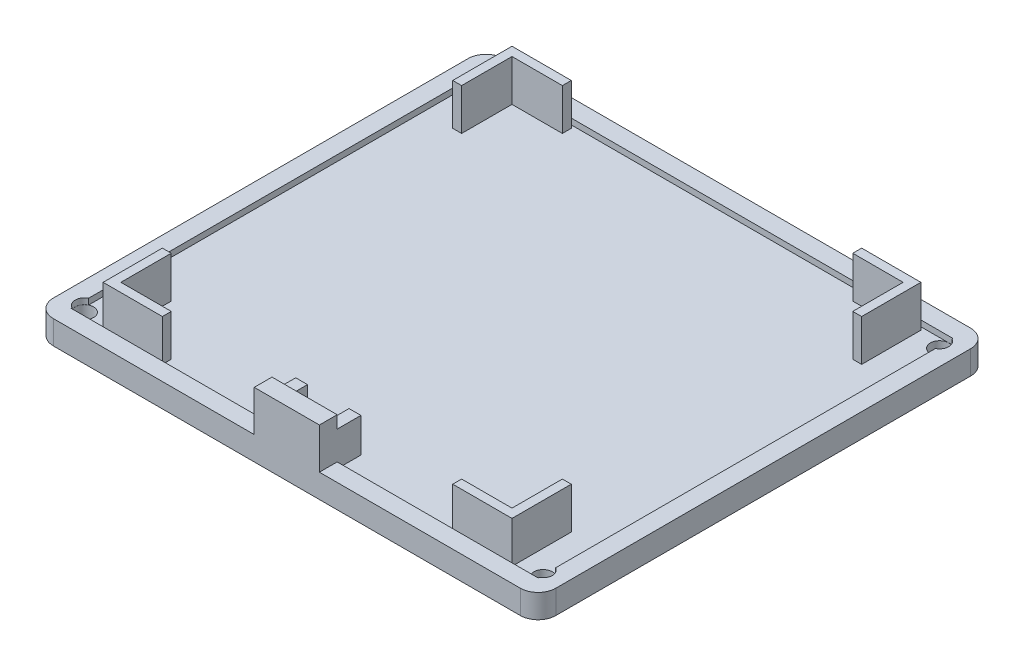
SolidWorks part; units mm, degrees
ref_plane "Front Plane" through (0, 0, 0) normal (0, 0, 1) x (1, 0, 0)
ref_plane "Top Plane" through (0, 0, 0) normal (0, 1, 0) x (1, 0, 0)
ref_plane "Right Plane" through (0, 0, 0) normal (1, 0, 0) x (0, 0, -1)
sketch "Sketch2" plane through (0, 0, 0) normal (0, 1, 0) x (1, 0, 0)
  line L1 (-42.4, 38) -> (42.4, 38)
  line L2 (-42.4, 38) -> (-42.4, -38)
  line L3 (-42.4, -38) -> (42.4, -38)
  line L4 (42.4, 38) -> (42.4, -38)
  line L5 (-42.4, 38) -> (42.4, -38) construction
  line L6 (-42.4, -38) -> (42.4, 38) construction
  line L7 (-38.7, -33.44) -> (38.7, -33.44) construction
  line L8 (-38.7, -33.44) -> (-38.7, 33.44) construction
  line L9 (-38.7, 33.44) -> (38.7, 33.44) construction
  line L10 (38.7, -33.44) -> (38.7, 33.44) construction
  line L11 (-38.7, -33.44) -> (38.7, 33.44) construction
  line L12 (-38.7, 33.44) -> (38.7, -33.44) construction
  circle A0 centre (38.7, 33.44) radius 1.55
  circle A1 centre (38.7, -33.44) radius 1.55
  circle A2 centre (-38.7, 33.44) radius 1.55
  circle A3 centre (-38.7, -33.44) radius 1.55
  point P0 (0, 0)
  point P5 (0, 0)
  dimension "D5" = 3.1
  dimension "D1" = 76
  dimension "D2" = 84.8
  dimension "D3" = 77.4
  dimension "D4" = 66.88
extrude "Boss-Extrude1" add sketch "Sketch2" along normal blind 3
sketch "Sketch3" plane through (0, 3, 0) normal (0, 1, 0) x (1, 0, 0)
  line L0 (-42.4, -38) -> (42.4, -38) construction
  line L1 (-5.5, -38) -> (5.5, -38)
  line L2 (-5.5, -38) -> (-5.5, -35)
  line L3 (-5.5, -35) -> (5.5, -35)
  line L4 (5.5, -38) -> (5.5, -35)
  line L5 (0, 0) -> (0, -35) construction
  dimension "D1" = 11
  dimension "D2" = 3
extrude "Boss-Extrude2" add sketch "Sketch3" along normal blind 7.9
fillet "Fillet1" radius 3 4 edges at (42.4, 1.5, -38) (-42.4, 1.5, -38) (42.4, 1.5, 38) (-42.4, 1.5, 38)
sketch "Sketch4" plane through (0, 3, 0) normal (0, 1, 0) x (1, 0, 0)
  line L0 (5.5, -38) -> (39.4, -38) construction
  line L1 (-5.5, -38) -> (5.5, -38) construction
  line L2 (-39.4, -38) -> (-5.5, -38) construction
  line L3 (42.4, -35) -> (42.4, 35) construction
  line L4 (-42.4, 35) -> (-42.4, -35) construction
  line L5 (39.4, 38) -> (-39.4, 38) construction
  line L6 (5.5, -38) -> (39.4, -38)
  line L25 (-5.5, -38) -> (5.5, -38)
  line L26 (-39.4, -38) -> (-5.5, -38)
  line L27 (42.4, -35) -> (42.4, 35)
  line L28 (-42.4, 35) -> (-42.4, -35)
  line L29 (39.4, 38) -> (-39.4, 38)
  line L30 (39.4, -35) -> (39.4, -34.8341)
  line L31 (39.4, 35) -> (-39.4, 35)
  line L32 (-39.4, 35) -> (-39.4, 34.8341)
  line L33 (-39.4, -35) -> (-5.5, -35)
  line L34 (-5.5, -35) -> (5.5, -35)
  line L35 (5.5, -35) -> (39.4, -35)
  line L36 (-39.4, 32.0459) -> (-39.4, -32.0459)
  line L37 (-39.4, 35) -> (-39.4, -35) construction
  line L38 (39.4, 34.8341) -> (39.4, 35)
  line L39 (39.4, -35) -> (39.4, 35) construction
  line L40 (39.4, -32.0459) -> (39.4, 32.0459)
  line L41 (-39.4, -34.8341) -> (-39.4, -35)
  arc A0 (39.4, -38) -> (42.4, -35) centre (39.4, -35) ccw construction
  arc A1 (-42.4, -35) -> (-39.4, -38) centre (-39.4, -35) ccw construction
  arc A2 (42.4, 35) -> (39.4, 38) centre (39.4, 35) ccw construction
  arc A3 (-39.4, 38) -> (-42.4, 35) centre (-39.4, 35) ccw construction
  arc A16 (39.4, -38) -> (42.4, -35) centre (39.4, -35) ccw
  arc A17 (-42.4, -35) -> (-39.4, -38) centre (-39.4, -35) ccw
  arc A18 (42.4, 35) -> (39.4, 38) centre (39.4, 35) ccw
  arc A19 (-39.4, 38) -> (-42.4, 35) centre (-39.4, 35) ccw
  arc A20 (-39.4, 34.8341) -> (-39.4, 32.0459) centre (-38.7, 33.44) ccw
  arc A21 (39.4, 32.0459) -> (39.4, 34.8341) centre (38.7, 33.44) ccw
  arc A22 (39.4, -34.8341) -> (39.4, -32.0459) centre (38.7, -33.44) ccw
  arc A23 (-39.4, -32.0459) -> (-39.4, -34.8341) centre (-38.7, -33.44) ccw
  arc A24 (39.4, -35) -> (39.4, -35) centre (39.4, -35) ccw
  arc A25 (39.4, 35) -> (39.4, 35) centre (39.4, 35) ccw
  arc A26 (-39.4, 35) -> (-39.4, 35) centre (-39.4, 35) ccw
  arc A27 (-39.4, -35) -> (-39.4, -35) centre (-39.4, -35) ccw
  dimension "D1" = 3
extrude "Boss-Extrude3" add sketch "Sketch4" along normal blind 1
sketch "Sketch9" plane through (0, 3, 0) normal (0, 1, 0) x (1, 0, 0)
  line L1 (-34.5, 34.5) -> (34.5, 34.5) construction
  line L2 (-34.5, 34.5) -> (-34.5, -34.5) construction
  line L3 (-34.5, -34.5) -> (34.5, -34.5) construction
  line L4 (34.5, 34.5) -> (34.5, -34.5) construction
  line L5 (-34.5, 34.5) -> (34.5, -34.5) construction
  line L6 (-34.5, -34.5) -> (34.5, 34.5) construction
  line L7 (-34.5, 34.5) -> (-24.5, 34.5)
  line L8 (-34.5, 34.5) -> (-34.5, 24.5)
  line L9 (-33, 33) -> (-24.5, 33)
  line L10 (-24.5, 34.5) -> (-24.5, 33)
  line L13 (-34.5, 24.5) -> (-33, 24.5)
  line L14 (-33, 33) -> (-33, 24.5)
  line L15 (34.5, 34.5) -> (24.5, 34.5)
  line L17 (33, 33) -> (24.5, 33)
  line L18 (24.5, 34.5) -> (24.5, 33)
  line L20 (34.5, 34.5) -> (34.5, 24.5)
  line L21 (34.5, 24.5) -> (33, 24.5)
  line L22 (33, 33) -> (33, 24.5)
  line L24 (34.5, -34.5) -> (34.5, -24.5)
  line L25 (34.5, -24.5) -> (33, -24.5)
  line L26 (33, -33) -> (33, -24.5)
  line L27 (34.5, -34.5) -> (24.5, -34.5)
  line L29 (33, -33) -> (24.5, -33)
  line L30 (24.5, -34.5) -> (24.5, -33)
  line L32 (-34.5, -34.5) -> (-34.5, -24.5)
  line L33 (-34.5, -24.5) -> (-33, -24.5)
  line L34 (-33, -33) -> (-33, -24.5)
  line L35 (-34.5, -34.5) -> (-24.5, -34.5)
  line L37 (-33, -33) -> (-24.5, -33)
  line L38 (-24.5, -34.5) -> (-24.5, -33)
  point P0 (0, 0)
  dimension "D1" = 69
  dimension "D2" = 1.5
  dimension "D3" = 10
extrude "Boss-Extrude5" add sketch "Sketch9" along normal blind 7
sketch "Sketch10" plane through (0, 0, 0) normal (0, -1, 0) x (1, 0, 0)
  circle A0 centre (-38.7, 33.44) radius 2.55
  circle A1 centre (38.7, 33.44) radius 2.55
  circle A2 centre (38.7, -33.44) radius 2.55
  circle A3 centre (-38.7, -33.44) radius 2.55
  dimension "D1" = 5.1
extrude "Cut-Extrude2" cut sketch "Sketch10" against normal blind 1
sketch "Sketch11" plane through (0, 0, 0) normal (0, -1, 0) x (1, 0, 0)
  text T0 "90W" font "Century Gothic" height in points 48
extrude "Cut-Extrude3" cut sketch "Sketch11" against normal blind 1
sketch "Sketch13" plane through (0, 3, 0) normal (0, 1, 0) x (1, 0, 0)
  line L1 (-5.5, -35) -> (-3.5, -35)
  line L2 (-5.5, -35) -> (-5.5, -31)
  line L3 (-5.5, -31) -> (-3.5, -31)
  line L4 (-3.5, -35) -> (-3.5, -31)
  line L5 (5.5, -35) -> (3.5, -35)
  line L6 (5.5, -35) -> (5.5, -31)
  line L7 (5.5, -31) -> (3.5, -31)
  line L8 (3.5, -35) -> (3.5, -31)
  dimension "D1" = 4
  dimension "D2" = 4
  dimension "D3" = 2
  dimension "D4" = 2
extrude "Boss-Extrude6" add sketch "Sketch13" along normal blind 5.8
